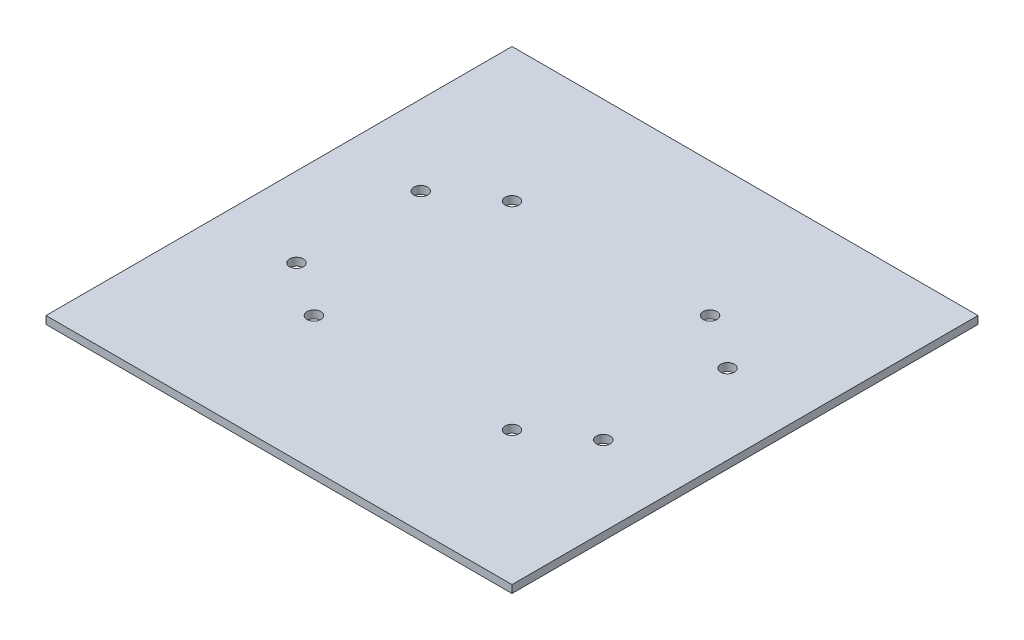
SolidWorks part; units mm, degrees
ref_plane "Front Plane" through (0, 0, 0) normal (0, 0, 1) x (1, 0, 0)
ref_plane "Top Plane" through (0, 0, 0) normal (0, 1, 0) x (1, 0, 0)
ref_plane "Right Plane" through (0, 0, 0) normal (1, 0, 0) x (0, 0, -1)
sketch "Sketch1" plane through (0, 0, 0) normal (0, 1, 0) x (1, 0, 0)
  line L1 (44.88, 74.7331) -> (164.88, 74.7331)
  line L2 (44.88, 74.7331) -> (44.88, -45.2669)
  line L3 (44.88, -45.2669) -> (164.88, -45.2669)
  line L4 (164.88, 74.7331) -> (164.88, -45.2669)
  dimension "D1" = 120
extrude "Boss-Extrude1" add sketch "Sketch1" along normal blind 2
sketch "Sketch2" plane through (0, 2, 0) normal (0, 1, 0) x (1, 0, 0)
  line L0 (65.38, 30.7331) -> (44.88, 30.7331) construction
  line L1 (65.38, -1.2669) -> (65.38, 30.7331) construction
  line L2 (65.38, 30.7331) -> (144.38, 30.7331) construction
  line L3 (144.38, 30.7331) -> (144.38, -1.2669) construction
  line L4 (144.38, -1.2669) -> (65.38, -1.2669) construction
  line L5 (44.88, 74.7331) -> (44.88, -45.2669) construction
  line L6 (144.38, 30.7331) -> (164.88, 30.7331) construction
  line L7 (164.88, -45.2669) -> (164.88, 74.7331) construction
  line L8 (74.6459, -45.2669) -> (74.6459, -1.2669) construction
  line L9 (44.88, -45.2669) -> (164.88, -45.2669) construction
  line L10 (119.5099, 30.7331) -> (119.5099, 74.7331) construction
  line L11 (164.88, 74.7331) -> (44.88, 74.7331) construction
  circle A0 centre (65.38, 30.7331) radius 1.775
  circle A1 centre (65.38, -1.2669) radius 1.775
  circle A2 centre (144.38, -1.2669) radius 1.775
  circle A3 centre (144.38, 30.7331) radius 1.775
  dimension "D3" = 3.55
  dimension "D1" = 32
  dimension "D2" = 79
extrude "Cut-Extrude1" cut sketch "Sketch2" against normal through all
sketch "Sketch3" plane through (0, 2, 0) normal (0, 1, 0) x (1, 0, 0)
  line L0 (79.38, -10.7669) -> (79.38, 40.2331) construction
  line L1 (79.38, 40.2331) -> (130.38, 40.2331) construction
  line L2 (130.38, 40.2331) -> (130.38, -10.7669) construction
  line L3 (130.38, -10.7669) -> (79.38, -10.7669) construction
  line L4 (104.88, -45.2669) -> (104.88, -10.7669) construction
  line L6 (44.88, -45.2669) -> (164.88, -45.2669) construction
  line L7 (44.88, 14.7331) -> (79.38, 14.7331) construction
  line L8 (44.88, 74.7331) -> (44.88, -45.2669) construction
  line L9 (104.88, 40.2331) -> (104.88, 74.7331) construction
  line L10 (164.88, 74.7331) -> (44.88, 74.7331) construction
  line L11 (130.38, 14.7331) -> (164.88, 14.7331) construction
  line L12 (164.88, -45.2669) -> (164.88, 74.7331) construction
  circle A0 centre (79.38, -10.7669) radius 1.775
  circle A1 centre (79.38, 40.2331) radius 1.775
  circle A2 centre (130.38, -10.7669) radius 1.775
  circle A3 centre (130.38, 40.2331) radius 1.775
  dimension "D3" = 3.55
  dimension "D1" = 51
  dimension "D2" = 51
extrude "Cut-Extrude2" cut sketch "Sketch3" against normal through all
